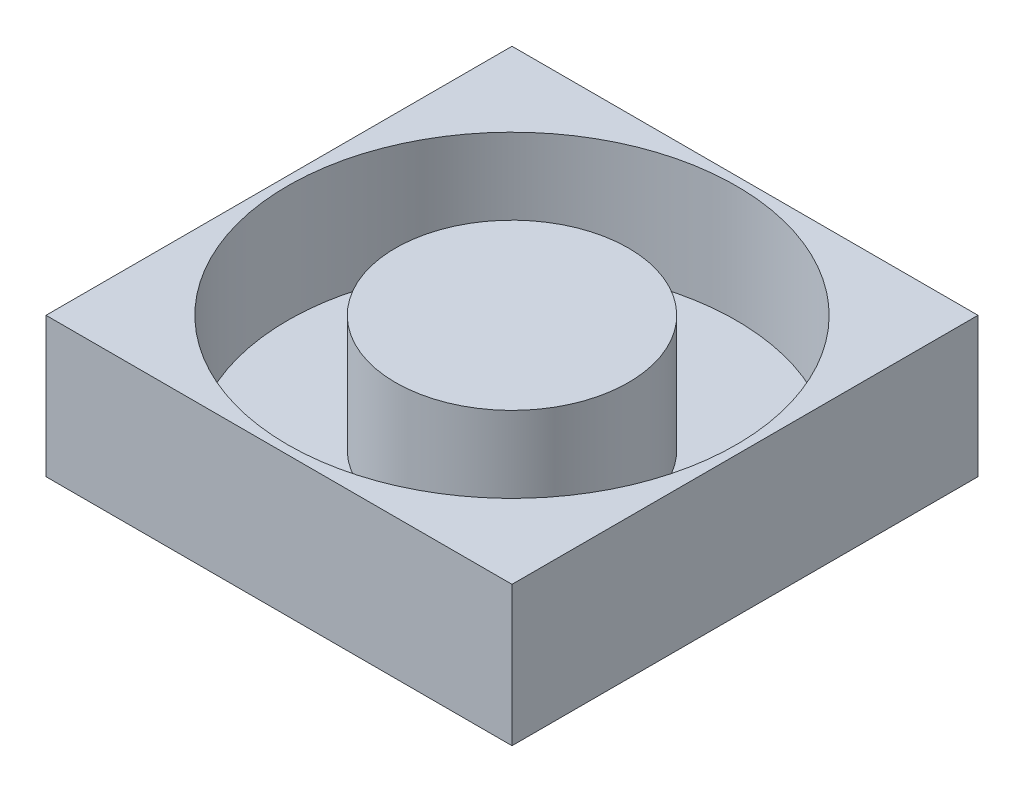
SolidWorks part; units mm, degrees
ref_plane "前视基准面" through (0, 0, 0) normal (0, 0, 1) x (1, 0, 0)
ref_plane "上视基准面" through (0, 0, 0) normal (0, 1, 0) x (1, 0, 0)
ref_plane "右视基准面" through (0, 0, 0) normal (1, 0, 0) x (0, 0, -1)
sketch "草图1" plane through (0, 0, 0) normal (0, 1, 0) x (1, 0, 0)
  line L1 (0, 0) -> (40, 0)
  line L2 (0, 0) -> (0, -40)
  line L3 (0, -40) -> (40, -40)
  line L4 (40, 0) -> (40, -40)
  dimension "D1" = 40
  dimension "D2" = 40
extrude "凸台-拉伸1" add sketch "草图1" along normal blind 12
sketch "草图2" plane through (0, 12, 0) normal (0, 1, 0) x (1, 0, 0)
  line L0 (0, 0) -> (40, -40) construction
  line L1 (40, 0) -> (0, -40) construction
  circle A0 centre (20, -20) radius 19.25
  circle A1 centre (20, -20) radius 10
  dimension "D1" = 38.5
  dimension "D2" = 20
extrude "切除-拉伸1" cut sketch "草图2" against normal blind 10
